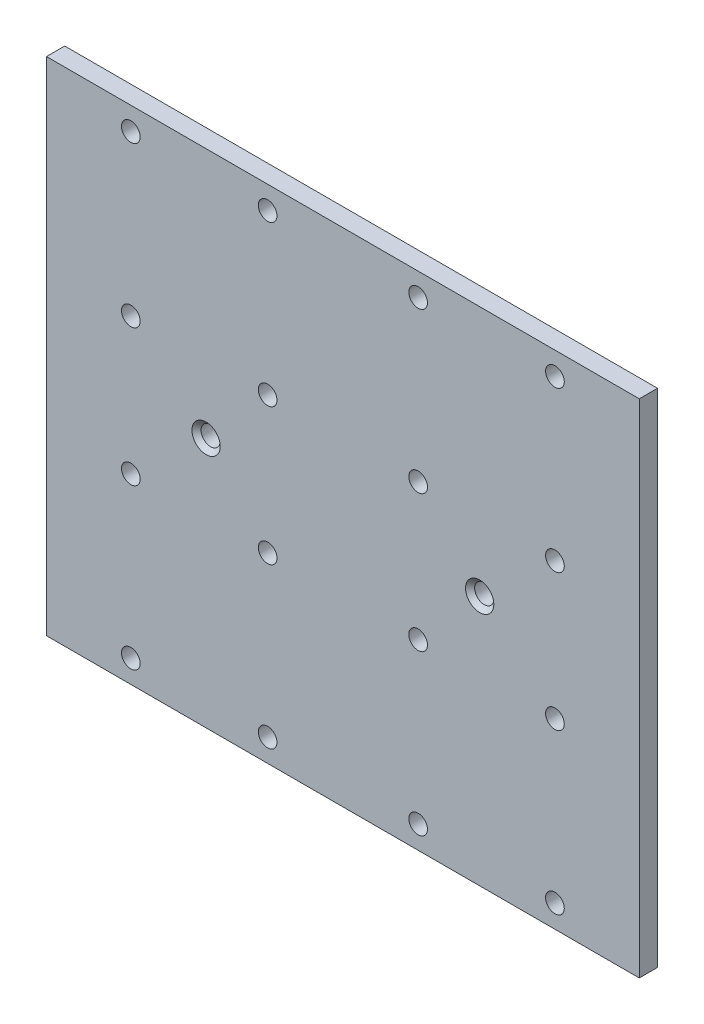
SolidWorks part; units mm, degrees
ref_plane "前视基准面" through (0, 0, 0) normal (0, 0, 1) x (1, 0, 0)
ref_plane "上视基准面" through (0, 0, 0) normal (0, 1, 0) x (1, 0, 0)
ref_plane "右视基准面" through (0, 0, 0) normal (1, 0, 0) x (0, 0, -1)
sketch "草图1" plane through (0, 0, 0) normal (0, 0, 1) x (1, 0, 0)
  line L1 (0, 0) -> (130, 0)
  line L2 (0, 0) -> (0, -110)
  line L3 (0, -110) -> (130, -110)
  line L4 (130, 0) -> (130, -110)
  dimension "D1" = 130
  dimension "D2" = 110
extrude "凸台-拉伸1" add sketch "草图1" along normal blind 5
sketch "草图3" plane through (0, 0, 0) normal (0, 0, -1) x (-1, 0, 0)
  line L0 (-130, 0) -> (0, 0) construction
  line L1 (-126.5, 0) -> (-66.5, 0)
  line L2 (-126.5, 0) -> (-126.5, -45)
  line L3 (-126.5, -45) -> (-66.5, -45)
  line L4 (-66.5, 0) -> (-66.5, -45)
  line L5 (0, -110) -> (-130, -110) construction
  line L6 (-63.5, 0) -> (-3.5, 0)
  line L7 (-63.5, 0) -> (-63.5, -45)
  line L8 (-63.5, -45) -> (-3.5, -45)
  line L9 (-3.5, 0) -> (-3.5, -45)
  line L10 (-126.5, -110) -> (-66.5, -110)
  line L11 (-126.5, -110) -> (-126.5, -65)
  line L12 (-126.5, -65) -> (-66.5, -65)
  line L13 (-66.5, -110) -> (-66.5, -65)
  line L14 (-130, -110) -> (-130, 0) construction
  line L15 (-63.5, -110) -> (-3.5, -110)
  line L16 (-63.5, -110) -> (-63.5, -65)
  line L17 (-63.5, -65) -> (-3.5, -65)
  line L18 (-3.5, -110) -> (-3.5, -65)
  line L19 (0, 0) -> (0, -110) construction
  dimension "D1" = 20
  dimension "D2" = 20
  dimension "D3" = 45
  dimension "D4" = 45
  dimension "D5" = 45
  dimension "D6" = 60
  dimension "D7" = 60
  dimension "D8" = 60
  dimension "D9" = 60
  dimension "D10" = 3
  dimension "D11" = 3.5
  dimension "D12" = 3.5
  dimension "D13" = 3
  dimension "D14" = 3.5
sketch "草图5" plane through (0, 0, 0) normal (0, 0, -1) x (-1, 0, 0)
  line L0 (-130, -55) -> (0, -55) construction
  line L3 (-65, 0) -> (-65, -110) construction
sketch "草图4" plane through (0, 0, 0) normal (0, 0, -1) x (-1, 0, 0)
  line L0 (-126.5, 0) -> (-66.5, 0) construction
  line L1 (-126.5, 0) -> (-126.5, -45) construction
  line L2 (-126.5, -45) -> (-66.5, -45) construction
  line L5 (-65, 200000) -> (-65, -200110) construction
  line L7 (-65, 200000) -> (-65, -200110) construction
  line L8 (-65, 8.1586) -> (-65, -135.8446) construction
  line L9 (-145.6256, -55) -> (43.0231, -55) construction
  circle A0 centre (-111.5, -5) radius 2.05
  circle A1 centre (-81.5, -5) radius 2.05
  circle A2 centre (-111.5, -40) radius 2.05
  circle A3 centre (-81.5, -40) radius 2.05
  circle A4 centre (-48.5, -40) radius 2.05
  circle A5 centre (-18.5, -40) radius 2.05
  circle A6 centre (-18.5, -5) radius 2.05
  circle A7 centre (-48.5, -5) radius 2.05
  circle A8 centre (-48.5, -105) radius 2.05
  circle A9 centre (-18.5, -105) radius 2.05
  circle A10 centre (-18.5, -70) radius 2.05
  circle A11 centre (-48.5, -70) radius 2.05
  circle A12 centre (-81.5, -70) radius 2.05
  circle A13 centre (-111.5, -70) radius 2.05
  circle A14 centre (-81.5, -105) radius 2.05
  circle A15 centre (-111.5, -105) radius 2.05
  dimension "D1" = 4.1
  dimension "D2" = 4.1
  dimension "D3" = 4.1
  dimension "D4" = 4.1
  dimension "D5" = 5
  dimension "D6" = 15
  dimension "D7" = 30
  dimension "D8" = 5
extrude "切除-拉伸1" cut sketch "草图4" against normal blind 5
chamfer "倒角1" [suppressed] distance 1 angle 45
chamfer "倒角2" distance 1 angle 45 20 edges at (65, -110, 0) (130, -55, 0) (65, 0, 0) (0, -55, 0) (109.45, -5, 0) (16.45, -105, 0) (16.45, -70, 0) (46.45, -70, 0) (83.55, -70, 0) (113.55, -105, 0) (83.55, -105, 0) (113.55, -70, 0) (50.55, -40, 0) (79.45, -40, 0) (109.45, -40, 0) (79.45, -5, 0) (20.55, -40, 0) (20.55, -5, 0) (50.55, -5, 0) (46.45, -105, 0)
sketch "草图6" plane through (0, 0, 0) normal (0, 0, -1) x (-1, 0, 0)
  line L0 (-200130, -55) -> (200000, -55) construction
  line L1 (-85, -65) -> (-105, -65)
  line L2 (-85, -65) -> (-85, -45)
  line L3 (-85, -45) -> (-105, -45)
  line L4 (-105, -65) -> (-105, -45)
  line L5 (-85, -65) -> (-105, -45) construction
  line L6 (-85, -45) -> (-105, -65) construction
  line L7 (-65, 200000) -> (-65, -200110) construction
  line L8 (-25, -65) -> (-45, -65)
  line L9 (-25, -65) -> (-25, -45)
  line L10 (-25, -45) -> (-45, -45)
  line L11 (-45, -65) -> (-45, -45)
  line L12 (-25, -65) -> (-45, -45) construction
  line L13 (-25, -45) -> (-45, -65) construction
  point P0 (-95, -55)
  point P7 (-35, -55)
  dimension "D1" = 20
  dimension "D2" = 20
  dimension "D3" = 20
  dimension "D4" = 20
  dimension "D5" = 40
  dimension "D6" = 20
extrude "凸台-拉伸2" add sketch "草图6" along normal blind 5
chamfer "倒角3" distance 3 angle 45 4 edges at (45, -55, 0) (25, -55, 0) (85, -55, 0) (105, -55, 0)
sketch "草图7" plane through (0, 0, -5) normal (0, 0, -1) x (-1, 0, 0)
  line L0 (-200130, -55) -> (200000, -55) construction
  line L1 (-85, -65) -> (-85, -45) construction
  line L2 (-25, -65) -> (-25, -45) construction
  circle A0 centre (-95, -55) radius 2.1
  circle A1 centre (-35, -55) radius 2.1
  dimension "D1" = 4.2
  dimension "D2" = 4.2
  dimension "D3" = 10
  dimension "D4" = 10
extrude "切除-拉伸2" cut sketch "草图7" against normal blind 49
chamfer "倒角4" distance 1 angle 45 2 edges at (97.1, -55, 5) (37.1, -55, 5)
sketch "草图8" plane through (0, 0, 0) normal (0, 0, -1) x (-1, 0, 0)
  line L0 (-200130, -55) -> (200000, -55) construction
  line L1 (-65.25, -110) -> (-64.75, -110)
  line L2 (-65.25, -110) -> (-65.25, 0)
  line L3 (-65.25, 0) -> (-64.75, 0)
  line L4 (-64.75, -110) -> (-64.75, 0)
  line L5 (-65.25, -110) -> (-64.75, 0) construction
  line L6 (-65.25, 0) -> (-64.75, -110) construction
  line L7 (-65, 200000) -> (-65, -200110) construction
  point P0 (-65, -55)
  dimension "D1" = 0.5
  dimension "D2" = 110
  dimension "D3" = 0.25
extrude "切除-拉伸3" cut sketch "草图8" against normal blind 0.5
